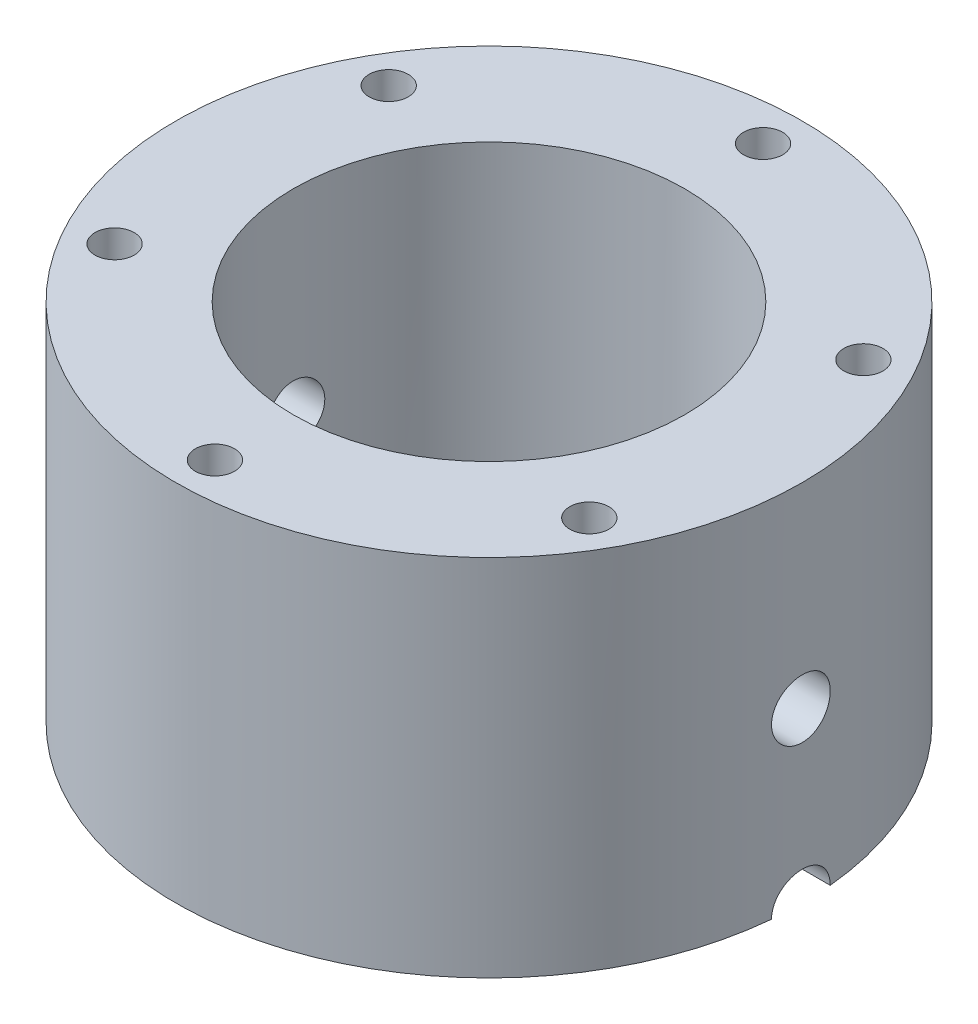
SolidWorks part; units mm, degrees
ref_plane "Front Plane" through (0, 0, 0) normal (0, 0, 1) x (1, 0, 0)
ref_plane "Top Plane" through (0, 0, 0) normal (0, 1, 0) x (1, 0, 0)
ref_plane "Right Plane" through (0, 0, 0) normal (1, 0, 0) x (0, 0, -1)
ref_axis "Centerline" through (0, 13.335, 0) along (0, -1, 0)
sketch "Sketch1" plane through (0, 0, 0) normal (0, 1, 0) x (1, 0, 0)
  circle A0 centre (0, 0) radius 20.32
  dimension "D1" = 40.64
extrude "Cylinder" add sketch "Sketch1" along normal blind 26.162
sketch "Sketch18" plane through (0, 26.162, 0) normal (0, 1, 0) x (1, 0, 0)
  circle A0 centre (0, 0) radius 12.7
  dimension "D1" = 25.4
extrude "Cut-Extrude10" cut sketch "Sketch18" against normal blind 23.368
sketch "Sketch19" plane through (0, 0, 0) normal (0, 0, 1) x (1, 0, 0)
  line L0 (-20.32, 0) -> (20.32, 0) construction
  circle A0 centre (12.573, 0) radius 1.905
  dimension "D2" = 3.81
  dimension "D1" = 12.573
revolve "Cut-Revolve7" cut sketch "Sketch19" angle 360 about axis through (0, 13.335, 0) along (0, -1, 0)
sketch "Sketch21" plane through (0, 26.162, 0) normal (0, 1, 0) x (1, 0, 0)
  line L0 (0, 23.819) -> (0, -25.5254) construction
  circle A0 centre (0, 17.78) radius 1.27
  dimension "D1" = 2.54
  dimension "D2" = 17.78
extrude "Cut-Extrude12" cut sketch "Sketch21" against normal up to next
pattern_circular "CirPattern4" count 6 over 360 about axis through (0, 0, 0) along (0, 1, 0) of "Cut-Extrude12"
sketch "Sketch22" plane through (0, 2.794, 0) normal (0, 1, 0) x (1, 0, 0)
  circle A0 centre (0, 0) radius 8.001
  dimension "D1" = 16.002
extrude "Cut-Extrude13" cut sketch "Sketch22" against normal up to next
ref_plane "Inlet Plane" through (20.32, 0, 0) normal (1, 0, 0) x (0, 0, -1)
sketch "Sketch25" plane through (20.32, 0, 0) normal (1, 0, 0) x (0, 0, -1)
  circle A0 centre (0, 0) radius 1.905
  dimension "D1" = 3.81
extrude "Cut-Extrude15" cut sketch "Sketch25" against normal up to next
pattern_circular "CirPattern6" count 2 over 360 about axis through (0, 0, 0) along (1, 0, 0) of "Cut-Extrude15"
sketch "Sketch26" plane through (20.32, 0, 0) normal (1, 0, 0) x (0, 0, -1)
  line L0 (0, 26.9973) -> (0, -3.7703) construction
  line L1 (20.32, 26.162) -> (-20.32, 26.162) construction
  circle A0 centre (0, 10.922) radius 1.905
  dimension "D2" = 3.81
  dimension "D1" = 15.24
extrude "Cut-Extrude16" cut sketch "Sketch26" against normal through all
sketch "Sketch27" plane through (0, 0, 0) normal (0, 0, 1) x (1, 0, 0)
  line L0 (-20.32, 26.162) -> (-20.32, 12.827) construction
  line L1 (20.32, 26.162) -> (-20.32, 26.162)
  line L2 (20.32, 26.162) -> (20.32, 23.622)
  line L3 (20.32, 23.622) -> (-20.32, 23.622)
  line L4 (-20.32, 26.162) -> (-20.32, 23.622)
  dimension "D1" = 2.54
extrude "Cut-Extrude17" cut sketch "Sketch27" against normal through all and the other way through all
